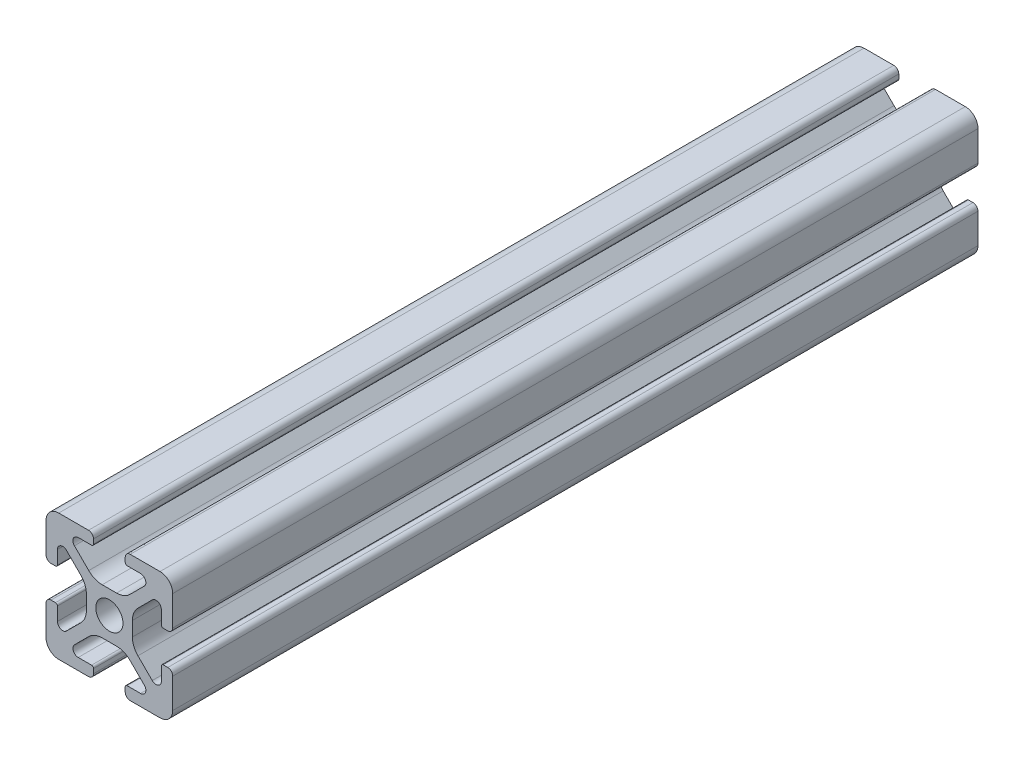
SolidWorks part; units mm, degrees
ref_plane "Front Plane" through (0, 0, 0) normal (0, 0, 1) x (1, 0, 0)
ref_plane "Top Plane" through (0, 0, 0) normal (0, 1, 0) x (1, 0, 0)
ref_plane "Right Plane" through (0, 0, 0) normal (1, 0, 0) x (0, 0, -1)
sketch "Sketch1" plane through (0, 0, 0) normal (0, 0, 1) x (1, 0, 0)
  line L2 (-9.9949, 7.9883) -> (-9.9949, 3.2893)
  line L3 (-7.9883, 9.9949) -> (-3.2893, 9.9949)
  line L4 (-2.5019, 9.2075) -> (-2.5019, 8.4963)
  line L5 (-2.8067, 8.1915) -> (-4.9149, 8.1915)
  line L6 (-5.5076, 6.7606) -> (-3.2528, 4.5058)
  line L7 (-6.7606, 5.5076) -> (-4.5058, 3.2528)
  line L8 (-8.1915, 4.9149) -> (-8.1915, 2.8067)
  line L9 (-8.4963, 2.5019) -> (-9.2075, 2.5019)
  line L11 (-1.1334, 3.6279) -> (1.1334, 3.6279)
  line L12 (-3.6279, 1.1334) -> (-3.6279, -1.1334)
  line L13 (8.4963, 2.5019) -> (9.2075, 2.5019)
  line L14 (8.1915, 4.9149) -> (8.1915, 2.8067)
  line L15 (9.9949, 7.9883) -> (9.9949, 3.2893)
  line L16 (7.9883, 9.9949) -> (3.2893, 9.9949)
  line L17 (2.5019, 9.2075) -> (2.5019, 8.4963)
  line L18 (2.8067, 8.1915) -> (4.9149, 8.1915)
  line L19 (3.6279, 1.1334) -> (3.6279, -1.1334)
  line L20 (5.5076, 6.7606) -> (3.2528, 4.5058)
  line L21 (6.7606, 5.5076) -> (4.5058, 3.2528)
  line L22 (-8.4963, -2.5019) -> (-9.2075, -2.5019)
  line L23 (-8.1915, -4.9149) -> (-8.1915, -2.8067)
  line L24 (-6.7606, -5.5076) -> (-4.5058, -3.2528)
  line L25 (-5.5076, -6.7606) -> (-3.2528, -4.5058)
  line L26 (-2.8067, -8.1915) -> (-4.9149, -8.1915)
  line L27 (-2.5019, -9.2075) -> (-2.5019, -8.4963)
  line L28 (-7.9883, -9.9949) -> (-3.2893, -9.9949)
  line L29 (-9.9949, -7.9883) -> (-9.9949, -3.2893)
  line L30 (9.9949, -7.9883) -> (9.9949, -3.2893)
  line L31 (7.9883, -9.9949) -> (3.2893, -9.9949)
  line L32 (2.5019, -9.2075) -> (2.5019, -8.4963)
  line L33 (2.8067, -8.1915) -> (4.9149, -8.1915)
  line L34 (5.5076, -6.7606) -> (3.2528, -4.5058)
  line L35 (6.7606, -5.5076) -> (4.5058, -3.2528)
  line L36 (8.1915, -4.9149) -> (8.1915, -2.8067)
  line L37 (8.4963, -2.5019) -> (9.2075, -2.5019)
  line L38 (-1.1334, -3.6279) -> (1.1334, -3.6279)
  circle A0 centre (0, 0) radius 2.1463
  arc A1 (-9.9949, 7.9883) -> (-7.9883, 9.9949) centre (-7.9883, 7.9883) cw
  arc A2 (-6.7606, 5.5076) -> (-8.1915, 4.9149) centre (-7.3533, 4.9149) ccw
  arc A3 (-4.9149, 8.1915) -> (-5.5076, 6.7606) centre (-4.9149, 7.3533) ccw
  arc A4 (-3.2893, 9.9949) -> (-2.5019, 9.2075) centre (-3.2893, 9.2075) cw
  arc A5 (-9.9949, 3.2893) -> (-9.2075, 2.5019) centre (-9.2075, 3.2893) ccw
  arc A6 (-8.1915, 2.8067) -> (-8.4963, 2.5019) centre (-8.4963, 2.8067) cw
  arc A7 (-2.5019, 8.4963) -> (-2.8067, 8.1915) centre (-2.8067, 8.4963) cw
  arc A8 (-1.1334, 3.6279) -> (-3.2528, 4.5058) centre (-1.1334, 6.6251) cw
  arc A9 (-3.6279, 1.1334) -> (-4.5058, 3.2528) centre (-6.6251, 1.1334) ccw
  arc A10 (8.1915, 2.8067) -> (8.4963, 2.5019) centre (8.4963, 2.8067) ccw
  arc A11 (9.9949, 3.2893) -> (9.2075, 2.5019) centre (9.2075, 3.2893) cw
  arc A12 (9.9949, 7.9883) -> (7.9883, 9.9949) centre (7.9883, 7.9883) ccw
  arc A13 (3.2893, 9.9949) -> (2.5019, 9.2075) centre (3.2893, 9.2075) ccw
  arc A14 (2.5019, 8.4963) -> (2.8067, 8.1915) centre (2.8067, 8.4963) ccw
  arc A15 (1.1334, 3.6279) -> (3.2528, 4.5058) centre (1.1334, 6.6251) ccw
  arc A16 (3.6279, 1.1334) -> (4.5058, 3.2528) centre (6.6251, 1.1334) cw
  arc A17 (6.7606, 5.5076) -> (8.1915, 4.9149) centre (7.3533, 4.9149) cw
  arc A18 (4.9149, 8.1915) -> (5.5076, 6.7606) centre (4.9149, 7.3533) cw
  arc A19 (-3.6279, -1.1334) -> (-4.5058, -3.2528) centre (-6.6251, -1.1334) cw
  arc A20 (-1.1334, -3.6279) -> (-3.2528, -4.5058) centre (-1.1334, -6.6251) ccw
  arc A21 (-2.5019, -8.4963) -> (-2.8067, -8.1915) centre (-2.8067, -8.4963) ccw
  arc A22 (-8.1915, -2.8067) -> (-8.4963, -2.5019) centre (-8.4963, -2.8067) ccw
  arc A23 (-9.9949, -3.2893) -> (-9.2075, -2.5019) centre (-9.2075, -3.2893) cw
  arc A24 (-3.2893, -9.9949) -> (-2.5019, -9.2075) centre (-3.2893, -9.2075) ccw
  arc A25 (-4.9149, -8.1915) -> (-5.5076, -6.7606) centre (-4.9149, -7.3533) cw
  arc A26 (-6.7606, -5.5076) -> (-8.1915, -4.9149) centre (-7.3533, -4.9149) cw
  arc A27 (-9.9949, -7.9883) -> (-7.9883, -9.9949) centre (-7.9883, -7.9883) ccw
  arc A28 (9.9949, -7.9883) -> (7.9883, -9.9949) centre (7.9883, -7.9883) cw
  arc A29 (6.7606, -5.5076) -> (8.1915, -4.9149) centre (7.3533, -4.9149) ccw
  arc A30 (4.9149, -8.1915) -> (5.5076, -6.7606) centre (4.9149, -7.3533) ccw
  arc A31 (3.2893, -9.9949) -> (2.5019, -9.2075) centre (3.2893, -9.2075) cw
  arc A32 (9.9949, -3.2893) -> (9.2075, -2.5019) centre (9.2075, -3.2893) ccw
  arc A33 (8.1915, -2.8067) -> (8.4963, -2.5019) centre (8.4963, -2.8067) cw
  arc A34 (2.5019, -8.4963) -> (2.8067, -8.1915) centre (2.8067, -8.4963) cw
  arc A35 (1.1334, -3.6279) -> (3.2528, -4.5058) centre (1.1334, -6.6251) cw
  arc A36 (3.6279, -1.1334) -> (4.5058, -3.2528) centre (6.6251, -1.1334) ccw
extrude "Boss-Extrude1" add sketch "Sketch1" along normal mid plane 126.9975
